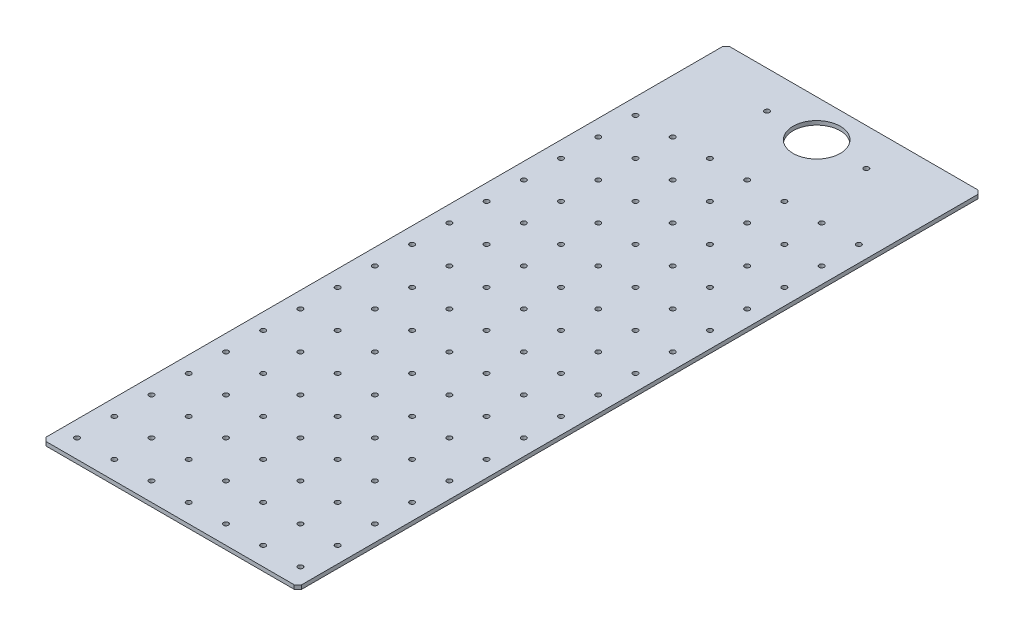
SolidWorks part; units mm, degrees
material "6061 合金"
ref_plane "正面" through (0, 0, 0) normal (0, 0, 1) x (1, 0, 0)
ref_plane "平面" through (0, 0, 0) normal (0, 1, 0) x (1, 0, 0)
ref_plane "右側面" through (0, 0, 0) normal (1, 0, 0) x (0, 0, -1)
sketch "ｽｹｯﾁ1" plane through (0, 0, 0) normal (0, 1, 0) x (1, 0, 0)
  line L0 (103, -275.5) -> (103, 275.5)
  line L1 (-103, -275.5) -> (103, -275.5)
  line L2 (-103, 275.5) -> (-103, -275.5)
  line L3 (103, 275.5) -> (-103, 275.5)
  dimension "D2" = 206
  dimension "D3" = 551
extrude "ﾎﾞｽ - 押し出し1" add sketch "ｽｹｯﾁ1" along normal blind 3.2
sketch "ｽｹｯﾁ2" plane through (0, 3.2, 0) normal (0, 1, 0) x (1, 0, 0)
  line L0 (-103, 245.5) -> (103, 245.5) construction
  line L1 (-103, 275.5) -> (-103, -275.5) construction
  line L2 (103, -275.5) -> (103, 275.5) construction
  line L3 (103, 275.5) -> (-103, 275.5) construction
  circle A0 centre (0, 245.5) radius 19
  circle A1 centre (0, 245.5) radius 40 construction
  circle A2 centre (-40, 245.5) radius 2
  circle A3 centre (40, 245.5) radius 2
  dimension "D1" = 38
  dimension "D3" = 80
  dimension "D4" = 4
  dimension "D2" = 30
extrude "ｶｯﾄ - 押し出し1" cut sketch "ｽｹｯﾁ2" against normal through all
sketch "ｽｹｯﾁ3" plane through (0, 3.2, 0) normal (0, 1, 0) x (1, 0, 0)
  line L2 (-103, -275.5) -> (103, -275.5) construction
  line L5 (0, -275.5) -> (0, -260.5) construction
  line L6 (-103, 275.5) -> (-103, -275.5) construction
  circle A0 centre (-90, -260.5) radius 2
  circle A1 centre (-60, -260.5) radius 2
  circle A2 centre (-30, -260.5) radius 2
  circle A3 centre (0, -260.5) radius 2
  circle A4 centre (30, -260.5) radius 2
  circle A5 centre (60, -260.5) radius 2
  circle A6 centre (90, -260.5) radius 2
  circle A7 centre (-60, -230.5) radius 2
  circle A8 centre (-30, -230.5) radius 2
  circle A9 centre (0, -230.5) radius 2
  circle A10 centre (30, -230.5) radius 2
  circle A11 centre (60, -230.5) radius 2
  circle A12 centre (90, -230.5) radius 2
  circle A13 centre (-60, -200.5) radius 2
  circle A14 centre (-30, -200.5) radius 2
  circle A15 centre (0, -200.5) radius 2
  circle A16 centre (30, -200.5) radius 2
  circle A17 centre (60, -200.5) radius 2
  circle A18 centre (90, -200.5) radius 2
  circle A19 centre (-60, -170.5) radius 2
  circle A20 centre (-30, -170.5) radius 2
  circle A21 centre (0, -170.5) radius 2
  circle A22 centre (30, -170.5) radius 2
  circle A23 centre (60, -170.5) radius 2
  circle A24 centre (90, -170.5) radius 2
  circle A25 centre (-60, -140.5) radius 2
  circle A26 centre (-30, -140.5) radius 2
  circle A27 centre (0, -140.5) radius 2
  circle A28 centre (30, -140.5) radius 2
  circle A29 centre (60, -140.5) radius 2
  circle A30 centre (90, -140.5) radius 2
  circle A31 centre (-60, -110.5) radius 2
  circle A32 centre (-30, -110.5) radius 2
  circle A33 centre (0, -110.5) radius 2
  circle A34 centre (30, -110.5) radius 2
  circle A35 centre (60, -110.5) radius 2
  circle A36 centre (90, -110.5) radius 2
  circle A37 centre (-90, -230.5) radius 2
  circle A38 centre (-90, -200.5) radius 2
  circle A39 centre (-90, -170.5) radius 2
  circle A40 centre (-90, -140.5) radius 2
  circle A41 centre (-90, -110.5) radius 2
  circle A42 centre (-90, -80.5) radius 2
  circle A43 centre (-60, -80.5) radius 2
  circle A44 centre (-30, -80.5) radius 2
  circle A45 centre (0, -80.5) radius 2
  circle A46 centre (30, -80.5) radius 2
  circle A47 centre (60, -80.5) radius 2
  circle A48 centre (90, -80.5) radius 2
  circle A49 centre (-90, -50.5) radius 2
  circle A50 centre (-60, -50.5) radius 2
  circle A51 centre (-30, -50.5) radius 2
  circle A52 centre (0, -50.5) radius 2
  circle A53 centre (30, -50.5) radius 2
  circle A54 centre (60, -50.5) radius 2
  circle A55 centre (90, -50.5) radius 2
  circle A56 centre (-90, -20.5) radius 2
  circle A57 centre (-60, -20.5) radius 2
  circle A58 centre (-30, -20.5) radius 2
  circle A59 centre (0, -20.5) radius 2
  circle A60 centre (30, -20.5) radius 2
  circle A61 centre (60, -20.5) radius 2
  circle A62 centre (90, -20.5) radius 2
  circle A63 centre (-90, 9.5) radius 2
  circle A64 centre (-60, 9.5) radius 2
  circle A65 centre (-30, 9.5) radius 2
  circle A66 centre (0, 9.5) radius 2
  circle A67 centre (30, 9.5) radius 2
  circle A68 centre (60, 9.5) radius 2
  circle A69 centre (90, 9.5) radius 2
  circle A70 centre (-90, 39.5) radius 2
  circle A71 centre (-60, 39.5) radius 2
  circle A72 centre (-30, 39.5) radius 2
  circle A73 centre (0, 39.5) radius 2
  circle A74 centre (30, 39.5) radius 2
  circle A75 centre (60, 39.5) radius 2
  circle A76 centre (90, 39.5) radius 2
  circle A77 centre (-90, 69.5) radius 2
  circle A78 centre (-60, 69.5) radius 2
  circle A79 centre (-30, 69.5) radius 2
  circle A80 centre (0, 69.5) radius 2
  circle A81 centre (30, 69.5) radius 2
  circle A82 centre (60, 69.5) radius 2
  circle A83 centre (90, 69.5) radius 2
  circle A84 centre (-90, 99.5) radius 2
  circle A85 centre (-60, 99.5) radius 2
  circle A86 centre (-30, 99.5) radius 2
  circle A87 centre (0, 99.5) radius 2
  circle A88 centre (30, 99.5) radius 2
  circle A89 centre (60, 99.5) radius 2
  circle A90 centre (90, 99.5) radius 2
  circle A91 centre (-90, 129.5) radius 2
  circle A92 centre (-60, 129.5) radius 2
  circle A93 centre (-30, 129.5) radius 2
  circle A94 centre (0, 129.5) radius 2
  circle A95 centre (30, 129.5) radius 2
  circle A96 centre (60, 129.5) radius 2
  circle A97 centre (90, 129.5) radius 2
  circle A98 centre (-90, 159.5) radius 2
  circle A99 centre (-60, 159.5) radius 2
  circle A100 centre (-30, 159.5) radius 2
  circle A101 centre (0, 159.5) radius 2
  circle A102 centre (30, 159.5) radius 2
  circle A103 centre (60, 159.5) radius 2
  circle A104 centre (90, 159.5) radius 2
  circle A105 centre (-90, 189.5) radius 2
  circle A106 centre (-60, 189.5) radius 2
  circle A107 centre (-30, 189.5) radius 2
  circle A108 centre (0, 189.5) radius 2
  circle A109 centre (30, 189.5) radius 2
  circle A110 centre (60, 189.5) radius 2
  circle A111 centre (90, 189.5) radius 2
  dimension "D1" = 4
  dimension "D2" = 90
  dimension "D3" = 15
  dimension "D4" = 13
  dimension "D5" = 7
  dimension "D6" = 16
extrude "グリッド穴" cut sketch "ｽｹｯﾁ3" against normal through all
chamfer "面取り1" distance 3 angle 45 4 edges at (-103, 1.6, -275.5) (103, 1.6, -275.5) (-103, 1.6, 275.5) (103, 1.6, 275.5)
sketch "ｽｹｯﾁ4" plane through (0, 3.2, 0) normal (0, 1, 0) x (1, 0, 0)
  circle A0 centre (-90, -260.5) radius 4
  circle A1 centre (-90, -260.5) radius 2 construction
  circle A2 centre (-90, -260.5) radius 2
  dimension "D1" = 8
extrude "ﾎﾞｽ - 押し出し2" [suppressed] add sketch "ｽｹｯﾁ4" against normal blind 5
pattern_linear "直線ﾊﾟﾀｰﾝ1" [suppressed] count 7 spacing 30 count 16 spacing 30
sketch "ｽｹｯﾁ5" plane through (0, 0, 0) normal (0, -1, 0) x (1, 0, 0)
  circle A4 centre (40, -245.5) radius 2
  circle A5 centre (40, -245.5) radius 4
  circle A6 centre (-40, -245.5) radius 2
  circle A7 centre (-40, -245.5) radius 4
  circle A8 centre (-40, -245.5) radius 2 construction
  point P11 (0, 0)
extrude "ﾎﾞｽ - 押し出し3" [suppressed] add sketch "ｽｹｯﾁ5" along normal up to surface (3 mm away)
